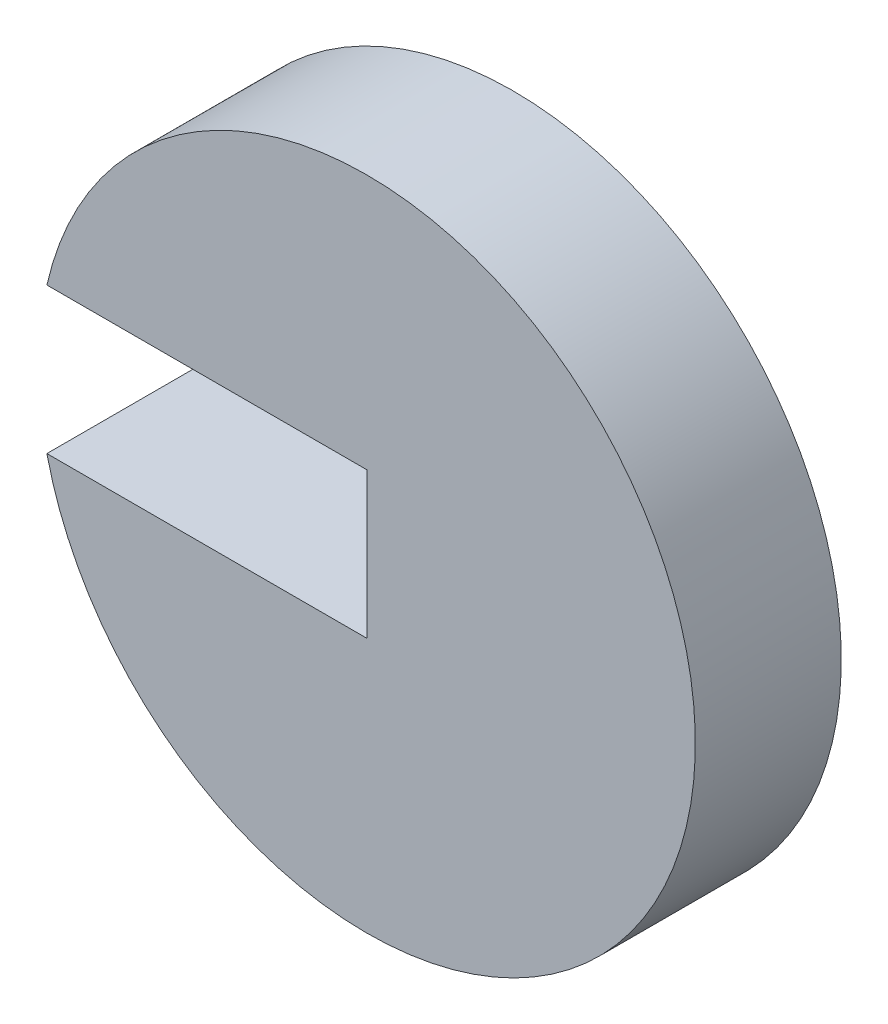
SolidWorks part; units mm, degrees
ref_plane "Alzado" through (0, 0, 0) normal (0, 0, 1) x (1, 0, 0)
ref_plane "Planta" through (0, 0, 0) normal (0, 1, 0) x (1, 0, 0)
ref_plane "Vista lateral" through (0, 0, 0) normal (1, 0, 0) x (0, 0, -1)
sketch "Croquis1" plane through (0, 0, 0) normal (0, 0, 1) x (1, 0, 0)
  line L12 (0, -1.5) -> (0, 1.5)
  line L13 (0, 1.5) -> (-6.5812, 1.5)
  line L14 (0, 0) -> (-15.1795, 0) construction
  line L15 (0, -1.5) -> (-6.5812, -1.5)
  arc A0 (-6.5812, -1.5) -> (-6.5812, 1.5) centre (0, 0) ccw
  dimension "D1" = 13.5
  dimension "D2" = 1.5
extrude "Saliente-Extruir1" add sketch "Croquis1" along normal blind 3
